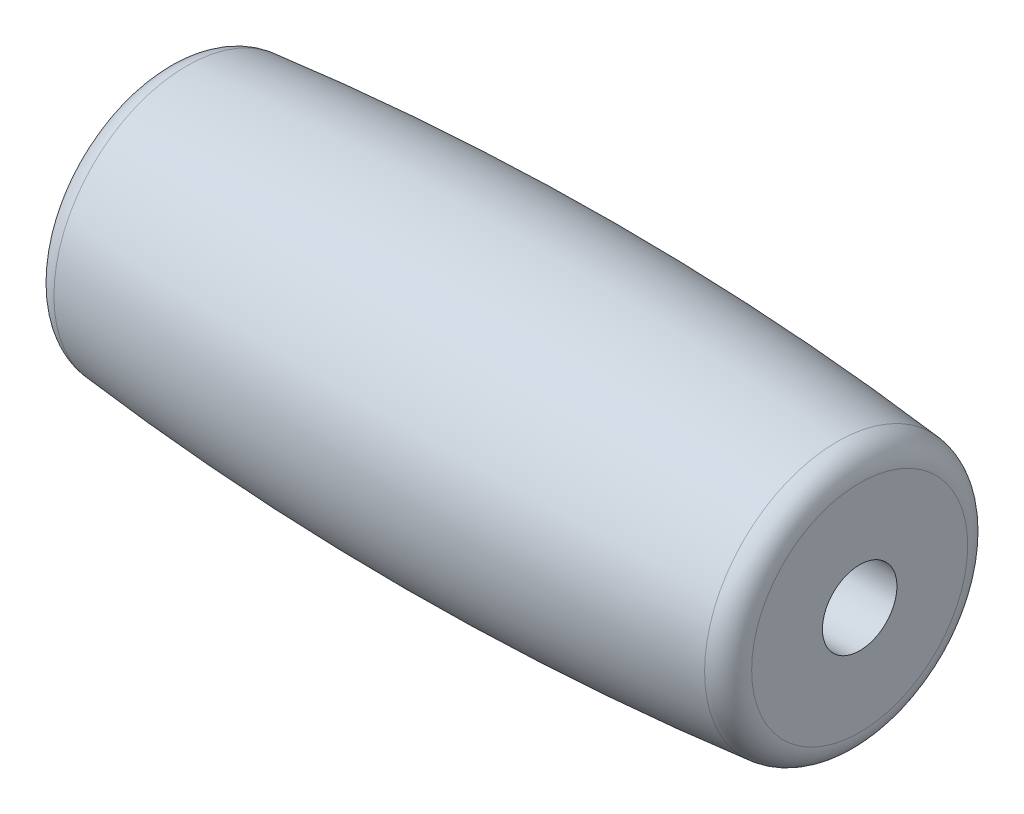
SolidWorks part; units mm, degrees
ref_plane "Front Plane" through (0, 0, 0) normal (0, 0, 1) x (1, 0, 0)
ref_plane "Top Plane" through (0, 0, 0) normal (0, 1, 0) x (1, 0, 0)
ref_plane "Right Plane" through (0, 0, 0) normal (1, 0, 0) x (0, 0, -1)
sketch "Sketch1" plane through (0, 0, 0) normal (0, 0, 1) x (1, 0, 0)
  line L0 (0, 6) -> (0, 0) construction
  line L1 (0, 0) -> (11.107, 0) construction
  line L2 (-14, 1.5) -> (14, 1.5)
  line L8 (14, 4.35) -> (14, 1.5)
  line L9 (-14, 4.3486) -> (-14, 1.5)
  arc A0 (-13.0999, 5.3436) -> (13.0998, 5.345) centre (0.0071, -125.1832) cw
  arc A1 (14, 4.35) -> (13.0998, 5.345) centre (13, 4.35) ccw
  arc A2 (-14, 4.3486) -> (-13.0999, 5.3436) centre (-13, 4.3486) cw
  point P10 (0, 1.5)
  point P16 (14, 5.25)
  point P19 (-14, 5.25)
  dimension "D7" = 1
  dimension "D1" = 1.5
  dimension "D2" = 2.8486
  dimension "D3" = 28
  dimension "D4" = 2.85
  dimension "D6" = 6
revolve "Revolve1" add sketch "Sketch1" angle 360 about L1
